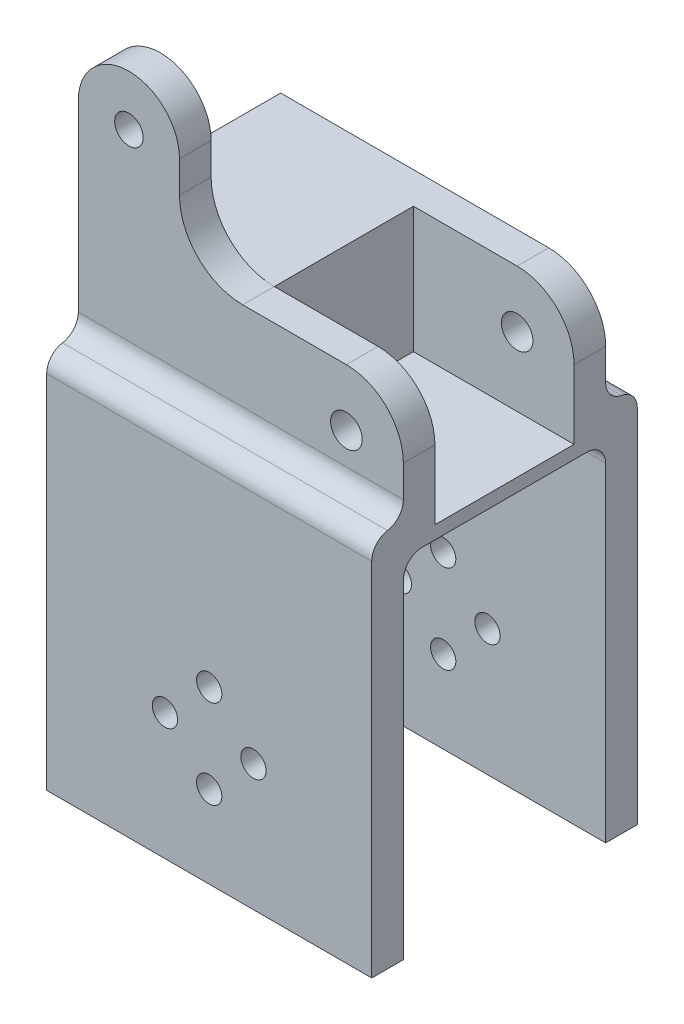
SolidWorks part; units mm, degrees
ref_plane "Ön Düzlem" through (0, 0, 0) normal (0, 0, 1) x (1, 0, 0)
ref_plane "Üst Düzlem" through (0, 0, 0) normal (0, 1, 0) x (1, 0, 0)
ref_plane "Sağ Düzlem" through (0, 0, 0) normal (1, 0, 0) x (0, 0, -1)
sketch "Sketch1" plane through (0, 0, 0) normal (0, 0, 1) x (1, 0, 0)
  line L0 (-21.2, 0) -> (21.2, 0) construction
  line L1 (-21.2, 33) -> (-21.2, 22)
  line L2 (-31.2, 12) -> (-27.5, 12) construction
  line L3 (-5.2, 33) -> (-5.2, 28)
  line L4 (4.8, 18) -> (21.2, 18)
  line L5 (-21.2, 22) -> (-21.2, 0)
  line L6 (-27.5, 0) -> (-21.2, 0) construction
  line L7 (30.2, 9) -> (30.2, -4)
  line L8 (30.2, -4) -> (-21.2, -4)
  line L9 (-21.2, -4) -> (-21.2, 0)
  arc A0 (30.2, 9) -> (21.2, 18) centre (21.2, 9) ccw
  arc A1 (-27.5, 0) -> (-27.5, 12) centre (-27.5, 6) cw construction
  circle A2 centre (21.2, 9) radius 2.5
  circle A4 centre (-13.2, 33) radius 2.25
  circle A5 centre (-13.2, 33) radius 8 construction
  arc A6 (-21.2, 33) -> (-5.2, 33) centre (-13.2, 33) cw
  arc A7 (-5.2, 28) -> (4.8, 18) centre (4.8, 28) ccw
  arc A8 (-21.2, 22) -> (-31.2, 12) centre (-31.2, 22) cw construction
  arc A9 (21.2, 0) -> (30.2, 9) centre (21.2, 9) ccw construction
  point P3 (0, 0)
  dimension "D2" = 9
  dimension "D3" = 6
  dimension "D4" = 4.5
  dimension "D5" = 5
  dimension "D6" = 33
  dimension "D8" = 16
  dimension "D9" = 10
  dimension "D1" = 42.4
  dimension "D7" = 34.4
  dimension "D10" = 4
extrude "Boss-Extrude1" add sketch "Sketch1" along normal mid plane 32
ref_plane "基准面1" through (0, 0, 0) normal (0, 0, 1) x (1, 0, 0)
sketch "草图7" plane through (0, 0, -16) normal (0, 0, -1) x (-1, 0, 0)
  line L0 (-4.8, 18) -> (21.2, 18)
  line L1 (21.2, 33) -> (21.2, -4) construction
  line L2 (21.2, 18) -> (21.2, 33)
  line L3 (5.2, 28) -> (5.2, 33) construction
  line L4 (5.2, 28) -> (5.2, 33)
  arc A0 (-4.8, 18) -> (5.2, 28) centre (-4.8, 28) ccw construction
  arc A1 (21.2, 33) -> (5.2, 33) centre (13.2, 33) ccw construction
  arc A2 (-4.8, 18) -> (5.2, 28) centre (-4.8, 28) ccw
  arc A3 (21.2, 33) -> (5.2, 33) centre (13.2, 33) ccw
extrude "切除-拉伸4" cut sketch "草图7" against normal blind 27
sketch "草图8" plane through (0, -4, 0) normal (0, -1, 0) x (1, 0, 0)
  line L0 (-21.2, 16) -> (30.2, 16) construction
  line L1 (-21.2, 16) -> (30.2, 16)
  line L2 (-21.2, 16) -> (-21.2, 21)
  line L3 (-21.2, 21) -> (30.2, 21)
  line L4 (30.2, 21) -> (30.2, 16)
  line L5 (-21.2, -16) -> (30.2, -16)
  line L6 (30.2, -16) -> (30.2, -21)
  line L7 (30.2, -21) -> (-21.2, -21)
  line L8 (-21.2, -21) -> (-21.2, -16)
  dimension "D1" = 5
  dimension "D2" = 5
extrude "凸台-拉伸1" add sketch "草图8" along normal blind 55 and the other way blind 5 separate body
combine bodies "组合1" operation type add bodies to combine 110 108 109
fillet "圆角1" radius 3 1 edges at (4.5, 1, -16)
fillet "圆角2" radius 3 1 edges at (4.5, 1, 16)
fillet "圆角3" radius 3 2 edges at (4.5, -4, 16) (4.5, -4, -16)
fillet "圆角4" radius 3 2 edges at (4.5, 1, 21) (4.5, 1, -21)
sketch "草图9" plane through (0, 0, 0) normal (0, 0, 1) x (1, 0, 0)
  line L0 (21.2, 18) -> (4.8, 18) construction
  line L1 (4.8, 18) -> (30.2, 18)
  line L2 (4.8, 18) -> (4.8, -1.9161)
  line L3 (4.8, -1.9161) -> (30.2, -1.9161)
  line L4 (30.2, 18) -> (30.2, -1.9161)
  arc A0 (-5.2, 28) -> (4.8, 18) centre (4.8, 28) ccw construction
extrude "切除-拉伸5" cut sketch "草图9" against normal mid plane 22
sketch "草图10" plane through (0, 0, -21) normal (0, 0, -1) x (-1, 0, 0)
  line L0 (21.2, -59) -> (-30.2, -59) construction
  line L1 (21.2, -59) -> (-30.2, -59) construction
  circle A0 centre (-4.5, -39) radius 7 construction
  circle A1 centre (2.5, -39) radius 2
  circle A2 centre (-4.5, -32) radius 2
  circle A3 centre (-4.5, -46) radius 2
  circle A4 centre (-11.5, -39) radius 2
  point P12 (0, 0)
  point P13 (-4.5, -59)
  dimension "D1" = 4
  dimension "D2" = 14
  dimension "D3" = 20
extrude "切除-拉伸6" cut sketch "草图10" against normal through all
